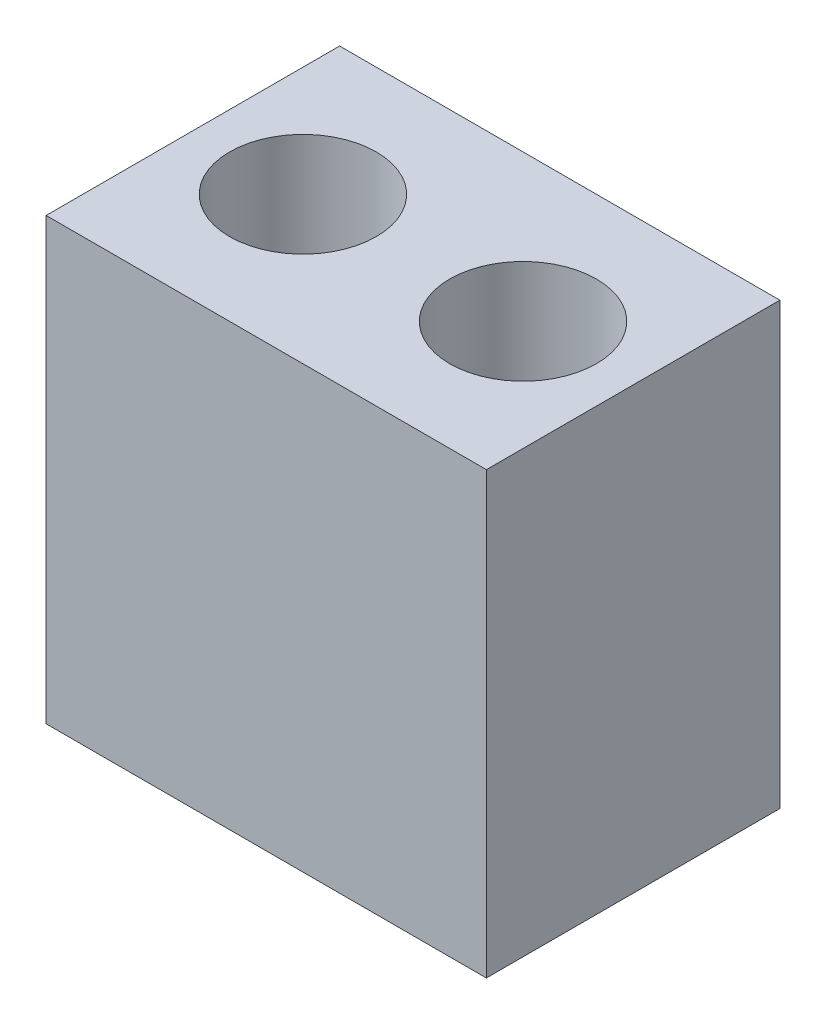
SolidWorks part; units mm, degrees
ref_plane "Front Plane" through (0, 0, 0) normal (0, 0, 1) x (1, 0, 0)
ref_plane "Top Plane" through (0, 0, 0) normal (0, 1, 0) x (1, 0, 0)
ref_plane "Right Plane" through (0, 0, 0) normal (1, 0, 0) x (0, 0, -1)
sketch "Sketch1" plane through (0, 0, 0) normal (0, 0, 1) x (1, 0, 0)
  line L1 (-15, 15) -> (15, 15)
  line L2 (-15, 15) -> (-15, -15)
  line L3 (-15, -15) -> (15, -15)
  line L4 (15, 15) -> (15, -15)
  line L5 (-15, 15) -> (15, -15) construction
  line L6 (-15, -15) -> (15, 15) construction
  point P0 (0, 0)
  dimension "D1" = 30
  dimension "D2" = 30
extrude "Boss-Extrude1" add sketch "Sketch1" along normal blind 20 contours L4 L3 L2 L1
sketch "Sketch2" plane through (0, 15, 0) normal (0, 1, 0) x (1, 0, 0)
  line L0 (0, 0) -> (0, -20) construction
  line L1 (-15, 0) -> (15, 0) construction
  line L2 (-15, -20) -> (15, -20) construction
  line L3 (0, -10) -> (-15, -10) construction
  line L4 (-15, -20) -> (-15, 0) construction
  line L5 (0, -10) -> (15, -10) construction
  line L6 (15, -20) -> (15, 0) construction
  circle A0 centre (-7.5, -10) radius 3
  circle A1 centre (7.5, -10) radius 2.53
  dimension "D1" = 6
  dimension "D2" = 5.06
extrude "Cut-Extrude1" cut sketch "Sketch2" against normal through all
sketch "Sketch3" plane through (0, 15, 0) normal (0, 1, 0) x (1, 0, 0)
  circle A0 centre (-7.5, -10) radius 5
  circle A1 centre (7.5, -10) radius 5
  dimension "D1" = 10
  dimension "D2" = 10
extrude "Cut-Extrude2" cut sketch "Sketch3" against normal blind 15
